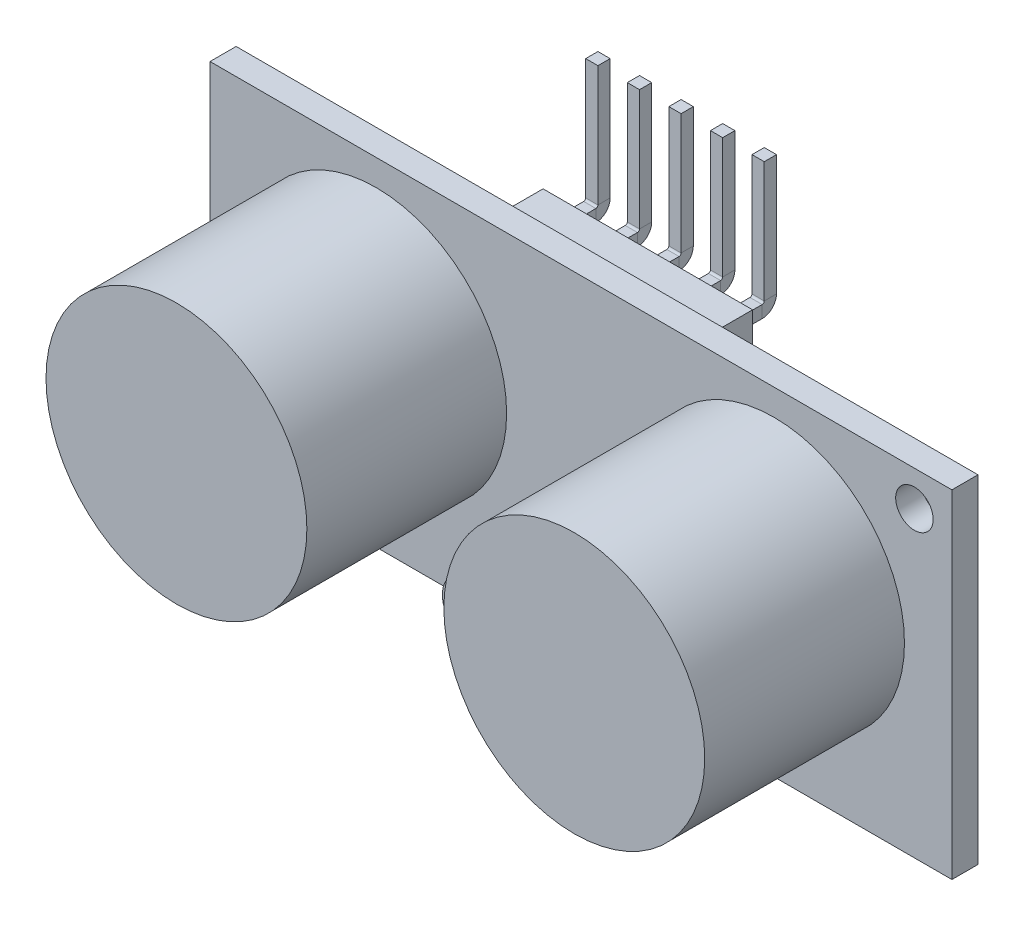
SolidWorks part; units mm, degrees
ref_plane "Front Plane" through (0, 0, 0) normal (0, 0, 1) x (1, 0, 0)
ref_plane "Top Plane" through (0, 0, 0) normal (0, 1, 0) x (1, 0, 0)
ref_plane "Right Plane" through (0, 0, 0) normal (1, 0, 0) x (0, 0, -1)
sketch "Sketch1" plane through (0, 0, 0) normal (0, 0, 1) x (1, 0, 0)
  line L1 (-22.75, -10.35) -> (22.75, -10.35)
  line L2 (-22.75, -10.35) -> (-22.75, 10.35)
  line L3 (-22.75, 10.35) -> (22.75, 10.35)
  line L4 (22.75, -10.35) -> (22.75, 10.35)
  line L5 (-22.75, -10.35) -> (22.75, 10.35) construction
  line L6 (-22.75, 10.35) -> (22.75, -10.35) construction
  point P0 (0, 0)
  dimension "D1" = 45.5
  dimension "D2" = 20.7
extrude "Boss-Extrude1" add sketch "Sketch1" along normal blind 1.6
sketch "Sketch2" plane through (0, 0, 1.6) normal (0, 0, 1) x (1, 0, 0)
  line L0 (0, 0.75) -> (22.75, 0.75) construction
  line L1 (-22.75, 10.35) -> (-22.75, -10.35) construction
  line L2 (-4.56, 0.75) -> (-4.56, -10.35) construction
  line L3 (-22.75, -10.35) -> (22.75, -10.35) construction
  line L4 (3.84, 0.75) -> (3.84, -10.35) construction
  line L5 (22.75, -10.35) -> (22.75, 10.35) construction
  line L6 (-12.56, -7.25) -> (-22.75, -7.25) construction
  line L7 (-12.56, 8.75) -> (-22.75, 8.75) construction
  circle A0 centre (-12.56, 0.75) radius 8
  circle A1 centre (11.84, 0.75) radius 8
  circle A2 centre (-21.655, 0.75) radius 1.095 construction
  circle A3 centre (21.295, 0.75) radius 1.455 construction
  dimension "D1" = 16
  dimension "D2" = 8.4
  dimension "D3" = 2.91
  dimension "D4" = 3.1
extrude "Boss-Extrude2" add sketch "Sketch2" along normal blind 12.25
sketch "Sketch3" plane through (0, 0, 1.6) normal (0, 0, 1) x (1, 0, 0)
  line L0 (-3.2, -7.35) -> (3.2, -7.35) construction
  line L1 (-3.2, -5.55) -> (3.2, -5.55)
  line L2 (-3.2, -9.15) -> (3.2, -9.15)
  line L3 (0, 0) -> (0, 10.35) construction
  line L5 (-22.75, -10.35) -> (22.75, -10.35) construction
  arc A0 (-3.2, -5.55) -> (-3.2, -9.15) centre (-3.2, -7.35) ccw
  arc A1 (3.2, -9.15) -> (3.2, -5.55) centre (3.2, -7.35) ccw
  point P2 (0, -7.35)
  dimension "D2" = 10
  dimension "D1" = 3.6
  dimension "D3" = 1.2
extrude "Boss-Extrude3" add sketch "Sketch3" along normal blind 3.5
sketch "Sketch4" plane through (0, 0, 0) normal (0, 0, -1) x (-1, 0, 0)
  line L1 (-22.75, 10.35) -> (22.75, 10.35) construction
  line L5 (-22.75, -10.35) -> (-22.75, 10.35) construction
  line L8 (22.75, 10.35) -> (22.75, -10.35) construction
  line L10 (22.75, -10.35) -> (-22.75, -10.35) construction
  circle A0 centre (-20.45, 8.2) radius 1.15
  circle A1 centre (20.6, -8.1) radius 1.15
  dimension "D1" = 2.3
  dimension "D2" = 1
  dimension "D3" = 1.15
  dimension "D4" = 1
  dimension "D5" = 1.1
extrude "Cut-Extrude1" cut sketch "Sketch4" against normal blind 3.5
sketch "Sketch5" plane through (0, 0, 0) normal (0, 0, -1) x (-1, 0, 0)
  line L0 (0, 0) -> (0, 8.4) construction
  line L1 (-6.425, 7.1) -> (6.425, 7.1)
  line L2 (-6.425, 7.1) -> (-6.425, 9.7)
  line L3 (-6.425, 9.7) -> (6.425, 9.7)
  line L4 (6.425, 7.1) -> (6.425, 9.7)
  line L5 (-6.425, 7.1) -> (6.425, 9.7) construction
  line L6 (-6.425, 9.7) -> (6.425, 7.1) construction
  line L7 (22.75, -10.35) -> (-22.75, -10.35) construction
  point P0 (0, 8.4)
  dimension "D1" = 12.85
  dimension "D2" = 2.6
  dimension "D3" = 17.45
extrude "Boss-Extrude4" add sketch "Sketch5" along normal blind 2.5
sketch "Sketch6" plane through (0, 0, -2.5) normal (0, 0, -1) x (-1, 0, 0)
  line L0 (-6.425, 7.1) -> (6.425, 7.1) construction
  line L1 (-6.425, 9.7) -> (-3.855, 9.7) construction
  line L2 (-6.425, 9.7) -> (-6.425, 7.1) construction
  line L3 (-6.425, 7.1) -> (-3.855, 7.1) construction
  line L4 (-3.855, 9.7) -> (-3.855, 7.1) construction
  line L6 (-4.765, 8.775) -> (-3.855, 9.7) construction
  line L7 (-5.515, 8.775) -> (-4.765, 8.775)
  line L8 (-5.515, 8.775) -> (-5.515, 8.025)
  line L9 (-5.515, 8.025) -> (-4.765, 8.025)
  line L10 (-4.765, 8.775) -> (-4.765, 8.025)
  line L11 (-4.765, 8.025) -> (-3.855, 7.1) construction
  line L12 (-5.515, 8.025) -> (-6.425, 7.1) construction
  line L13 (-6.425, 9.7) -> (-5.515, 8.775) construction
  line L14 (-5.14, 9.7) -> (-5.14, 7.1) construction
  dimension "D1" = 2.57
  dimension "D2" = 0.75
ref_plane "Plane1" through (5.14, 0, 0) normal (1, 0, 0) x (0, -1, 0)
sketch "Sketch7" plane through (5.14, 0, 0) normal (1, 0, 0) x (0, -1, 0)
  line L0 (-8.4, 2.5) -> (-8.4, 4.7661) construction
  line L1 (-8.775, 2.5) -> (-8.025, 2.5) construction
  line L2 (-8.4, 2.5) -> (-8.4, 4)
  line L3 (-8.9, 4.5) -> (-16.3, 4.5)
  arc A0 (-8.9, 4.5) -> (-8.4, 4) centre (-8.9, 4) cw
  point P8 (-8.4, 4.5)
  dimension "D3" = 0.5
  dimension "D1" = 2
  dimension "D2" = 7.9
sweep "Sweep17" add profiles "Sketch6" path "Sketch7"
pattern_linear "LPattern1" count 5 spacing 2.55 along (-1, 0, 0) of "Sweep17"
